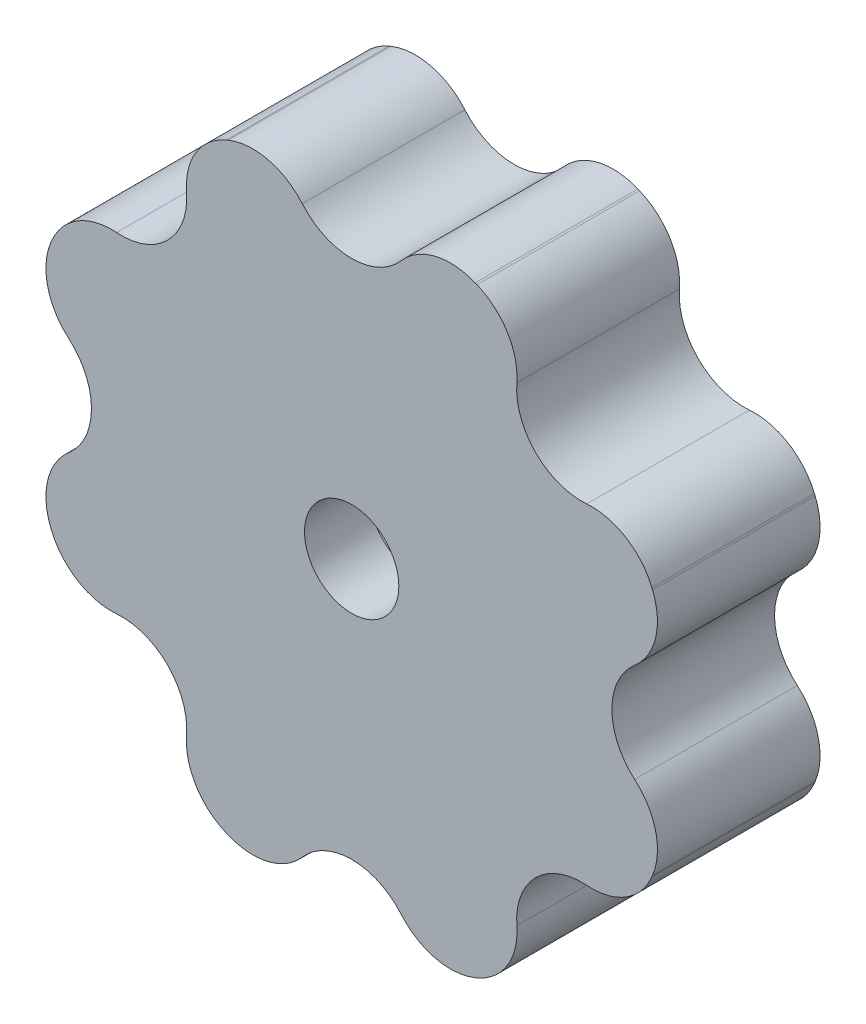
SolidWorks part; units mm, degrees
ref_plane "Спереди" through (0, 0, 0) normal (0, 0, 1) x (1, 0, 0)
ref_plane "Сверху" through (0, 0, 0) normal (0, 1, 0) x (1, 0, 0)
ref_plane "Справа" through (0, 0, 0) normal (1, 0, 0) x (0, 0, -1)
sketch "Эскиз1" plane through (0, 0, 0) normal (0, 0, 1) x (1, 0, 0)
  circle A0 centre (0, 0) radius 10
  arc A1 (-1.99, 9.8) -> (1.99, 9.8) centre (0, 10) ccw
  arc A2 (5.5225, 8.3368) -> (8.3368, 5.5225) centre (7.0711, 7.0711) ccw
  arc A3 (9.8, 1.99) -> (9.8, -1.99) centre (10, 0) ccw
  arc A4 (8.3368, -5.5225) -> (5.5225, -8.3368) centre (7.0711, -7.0711) ccw
  arc A5 (1.99, -9.8) -> (-1.99, -9.8) centre (0, -10) ccw
  arc A6 (-5.5225, -8.3368) -> (-8.3368, -5.5225) centre (-7.0711, -7.0711) ccw
  arc A7 (-9.8, -1.99) -> (-9.8, 1.99) centre (-10, 0) ccw
  arc A8 (-8.3368, 5.5225) -> (-5.5225, 8.3368) centre (-7.0711, 7.0711) ccw
  circle A9 centre (0, 0) radius 1.45
  point P30 (0, 0)
  dimension "D1" = 20
  dimension "D2" = 2
  dimension "D4" = 2.9
  dimension "D3" = 8
extrude "Бобышка-Вытянуть1" add sketch "Эскиз1" along normal blind 5 contours A8 A0 A7 A6 A5 A4 A3 A2 A1 A9
fillet "Скругление2" radius 2 16 edges at (5.5225, 8.3368, 2.5) (8.3368, 5.5225, 2.5) (9.8, 1.99, 2.5) (9.8, -1.99, 2.5) (8.3368, -5.5225, 2.5) (5.5225, -8.3368, 2.5) (1.99, -9.8, 2.5) (-1.99, -9.8, 2.5) (-5.5225, -8.3368, 2.5) (-8.3368, -5.5225, 2.5) (-9.8, -1.99, 2.5) (-9.8, 1.99, 2.5) (-8.3368, 5.5225, 2.5) (-5.5225, 8.3368, 2.5) (-1.99, 9.8, 2.5) (1.99, 9.8, 2.5)
sketch "Эскиз2" plane through (0, 0, 0) normal (0, 0, -1) x (-1, 0, 0)
  line L1 (0, 3.1754) -> (-2.75, 1.5877)
  line L2 (-2.75, 1.5877) -> (-2.75, -1.5877)
  line L3 (-2.75, -1.5877) -> (0, -3.1754)
  line L4 (0, -3.1754) -> (2.75, -1.5877)
  line L5 (2.75, -1.5877) -> (2.75, 1.5877)
  line L6 (2.75, 1.5877) -> (0, 3.1754)
  circle A0 centre (0, 0) radius 2.75 construction
  dimension "D1" = 5.5
extrude "Вырез-Вытянуть1" cut sketch "Эскиз2" against normal offset from surface (3 mm away) 2 up to face at (1.45, 0, 5)
